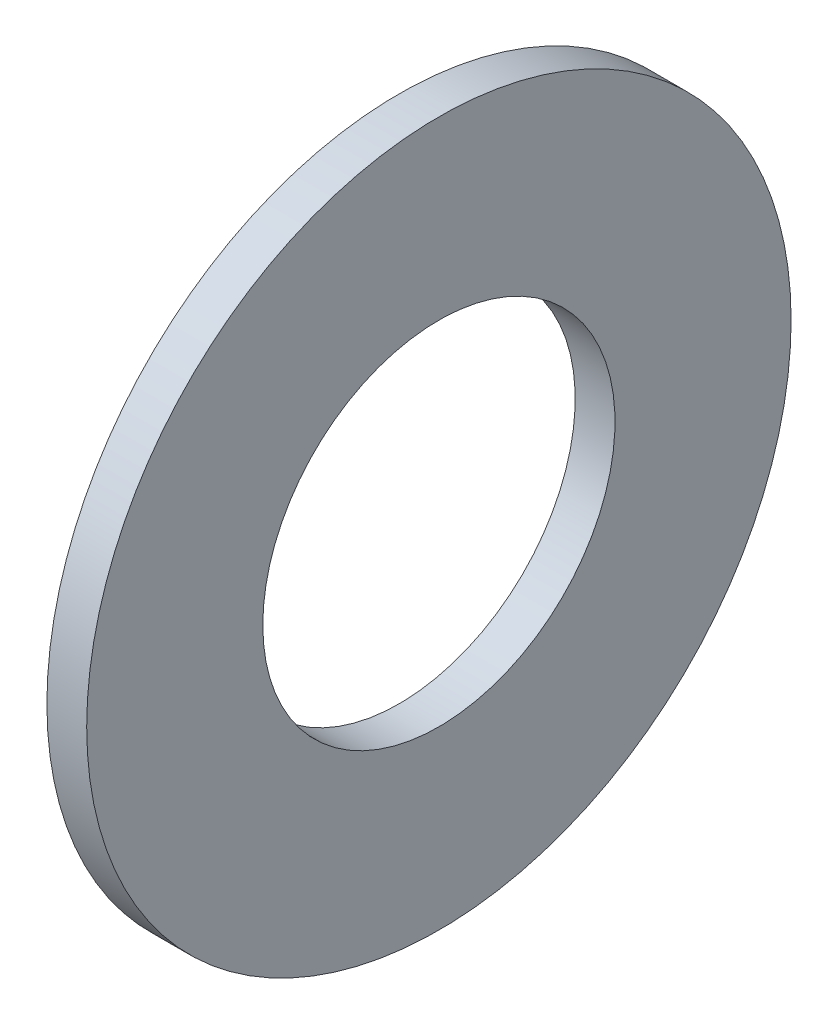
SolidWorks part; units mm, degrees
material "AISI 1020"
ref_plane "Front Plane" through (0, 0, 0) normal (0, 0, 1) x (1, 0, 0)
ref_plane "Top Plane" through (0, 0, 0) normal (0, 1, 0) x (1, 0, 0)
ref_plane "Right Plane" through (0, 0, 0) normal (1, 0, 0) x (0, 0, -1)
sketch "Sketch1" plane through (0, 0, 0) normal (1, 0, 0) x (0, 0, -1)
  circle A0 centre (0, 0) radius 13.4874
  circle A1 centre (0, 0) radius 6.7437
  dimension "OD" = 26.9748
  dimension "ID" = 13.4874
extrude "Boss-Extrude2" add sketch "Sketch1" along normal blind 1.524
